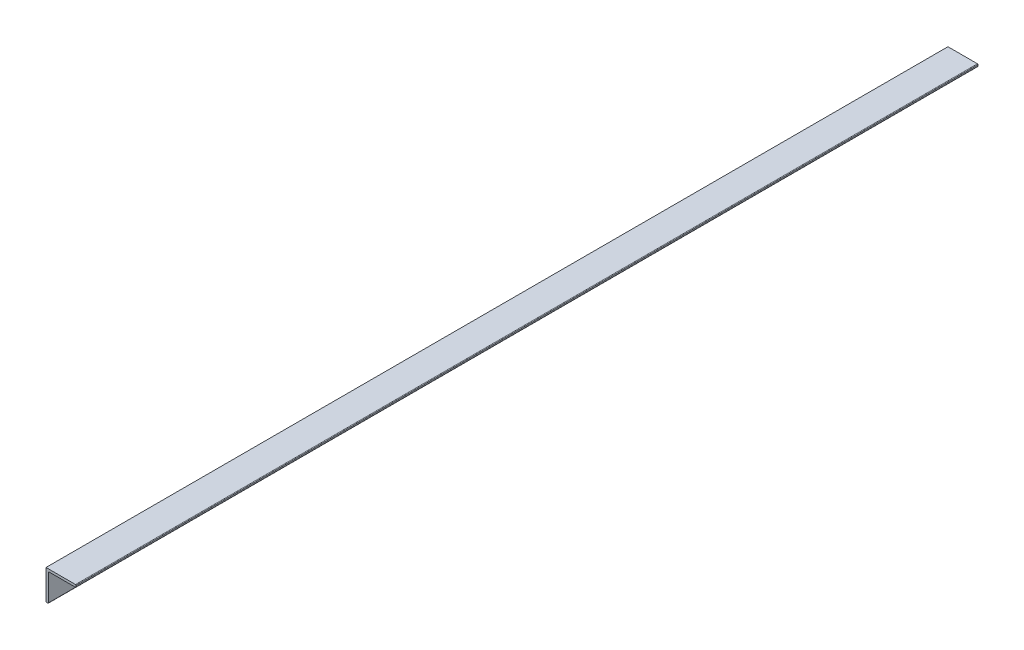
SolidWorks part; units mm, degrees
material "1060-H12"
ref_plane "Спереди" through (0, 0, 0) normal (0, 0, 1) x (1, 0, 0)
ref_plane "Сверху" through (0, 0, 0) normal (0, 1, 0) x (1, 0, 0)
ref_plane "Справа" through (0, 0, 0) normal (1, 0, 0) x (0, 0, -1)
sketch "Эскиз1" plane through (0, 0, 0) normal (0, 0, 1) x (1, 0, 0)
  line L0 (10, 14.5) -> (10, 13.5)
  line L2 (-15, -9.5) -> (-15, 15)
  line L3 (-15, 15) -> (9.5, 15)
  line L5 (-15, -15) -> (15, 15) construction
  line L6 (-15, 15) -> (15, -15) construction
  line L7 (-14.5, -10) -> (-13.5, -10)
  line L8 (9.5, 13) -> (-12.5, 13)
  line L9 (-13, 12.5) -> (-13, -9.5)
  arc A0 (-13.5, -10) -> (-13, -9.5) centre (-13.5, -9.5) ccw
  arc A1 (-14.5, -10) -> (-15, -9.5) centre (-14.5, -9.5) cw
  arc A2 (10, 13.5) -> (9.5, 13) centre (9.5, 13.5) cw
  arc A3 (9.5, 15) -> (10, 14.5) centre (9.5, 14.5) cw
  arc A4 (-12.5, 13) -> (-13, 12.5) centre (-12.5, 12.5) ccw
  point P0 (0, 0)
  point P23 (-13, 13)
  dimension "D4" = 0.5
  dimension "D5" = 0.5
  dimension "D1" = 30
  dimension "D2" = 25
  dimension "D3" = 25
extrude "Бобышка-Вытянуть1" add sketch "Эскиз1" along normal blind 750
